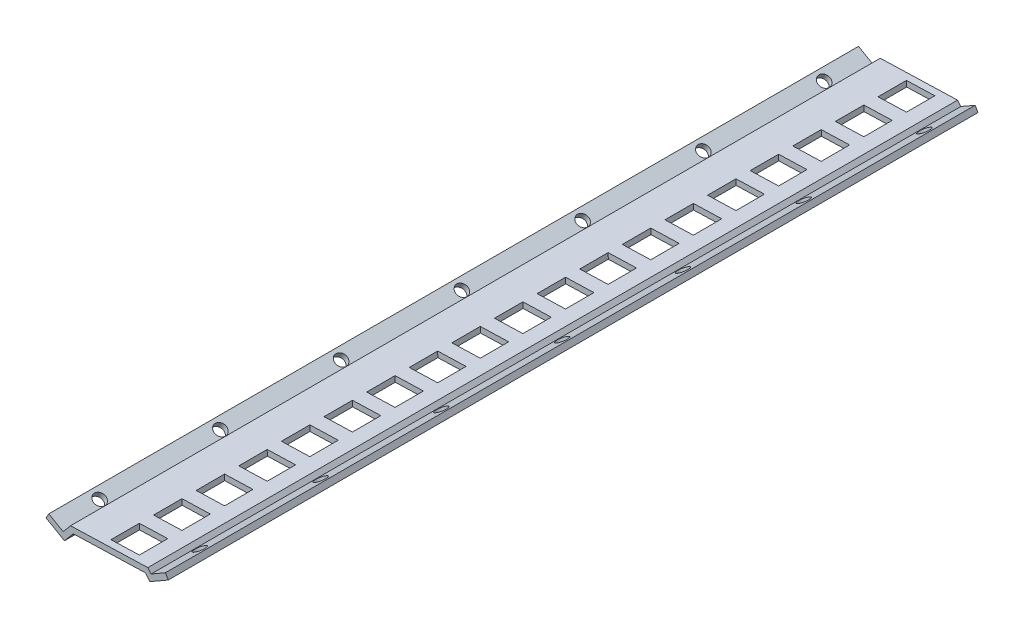
SolidWorks part; units mm, degrees
ref_plane "Front Plane" through (0, 0, 0) normal (0, 0, 1) x (1, 0, 0)
ref_plane "Top Plane" through (0, 0, 0) normal (0, 1, 0) x (1, 0, 0)
ref_plane "Right Plane" through (0, 0, 0) normal (1, 0, 0) x (0, 0, -1)
sketch "Sketch1" plane through (0, 0, 0) normal (0, 0, 1) x (1, 0, 0)
  line L0 (-7.5607, -2.2972) -> (8.7664, -1.7887)
  line L1 (8.7664, -1.7887) -> (9.4578, -2.6126)
  line L2 (9.4578, -2.6126) -> (12.4829, -0.866)
  line L3 (-7.5607, -2.2972) -> (-9.1175, -4.1524)
  line L4 (-9.1175, -4.1524) -> (-12.1426, -2.4059)
  line L5 (9.1858, -4.1553) -> (13.0829, -1.9053)
  line L6 (8.2216, -3.0062) -> (9.1858, -4.1553)
  line L7 (-6.9867, -3.4799) -> (8.2216, -3.0062)
  line L8 (-6.9867, -3.4799) -> (-8.8455, -5.6951)
  line L9 (-8.8455, -5.6951) -> (-12.7426, -3.4451)
  line L10 (13.0829, -1.9053) -> (12.4829, -0.866)
  line L11 (-12.1426, -2.4059) -> (-12.7426, -3.4451)
  line L12 (6.7957, -5.5352) -> (13.0829, -1.9053) construction
  line L13 (-15.4113, -1.9043) -> (-9.1242, -5.5342) construction
  line L15 (-7.1326, -17.6898) -> (6.8606, -17.2539) construction
  line L16 (-12.2753, -6.8158) -> (-8.0994, 0.4171) construction
  line L17 (12.6236, -5.286) -> (9.169, 0.6976) construction
  point P17 (-7.415, -0.2947)
  dimension "D1" = 4.5
  dimension "D2" = 4.5
  dimension "D3" = 100
  dimension "D4" = 120
  dimension "D5" = 100
  dimension "D6" = 2.0881
  dimension "D8" = 1.5
  dimension "D9" = 2.09
  dimension "D7" = 1.2
extrude "Boss-Extrude1" add sketch "Sketch1" along normal blind 171
sketch "Sketch2" plane through (3.4957, -6.0548, 0) normal (-0.5, 0.866, 0) x (0.866, 0.5, 0)
  line L0 (10.3775, -171) -> (6.8844, -171) construction
  line L1 (10.3775, -171) -> (10.3775, 0) construction
  circle A0 centre (8.3775, -162) radius 1.25
  dimension "D1" = 2.5
  dimension "D3" = 2
  dimension "D2" = 9
extrude "Cut-Extrude1" cut sketch "Sketch2" against normal blind 10 contours A0
sketch "Sketch4" plane through (-4.0774, -7.0623, 0) normal (0.5, 0.866, 0) x (0.866, -0.5, 0)
  line L0 (-9.3128, -171) -> (-9.3128, 0) construction
  line L1 (-5.8197, -171) -> (-9.3128, -171) construction
  circle A0 centre (-7.3128, -162) radius 1.25
  dimension "D1" = 2
  dimension "D2" = 2.5
  dimension "D3" = 9
extrude "Cut-Extrude2" cut sketch "Sketch4" against normal blind 10
pattern_linear "LPattern1" count 7 spacing 25.5 along (0, 0, -1) of "Cut-Extrude2", "Cut-Extrude1"
sketch "Sketch5" plane through (0.0642, -2.0597, 0) normal (-0.0311, 0.9995, 0) x (0.9995, 0.0311, 0)
  line L0 (8.7065, -171) -> (-7.6286, -171) construction
  line L1 (-0.5935, -163.5) -> (5.4065, -163.5)
  line L2 (-0.5935, -163.5) -> (-0.5935, -169.5)
  line L3 (-0.5935, -169.5) -> (5.4065, -169.5)
  line L4 (5.4065, -163.5) -> (5.4065, -169.5)
  line L5 (8.7065, -171) -> (8.7065, 0) construction
  point P4 (5.4065, -166.5)
  dimension "D1" = 4.5
  dimension "D2" = 6
  dimension "D3" = 6
  dimension "D4" = 3.3
extrude "Cut-Extrude3" cut sketch "Sketch5" against normal blind 10
pattern_linear "LPattern2" count 19 spacing 9 along (0, 0, -1) of "Cut-Extrude3"
